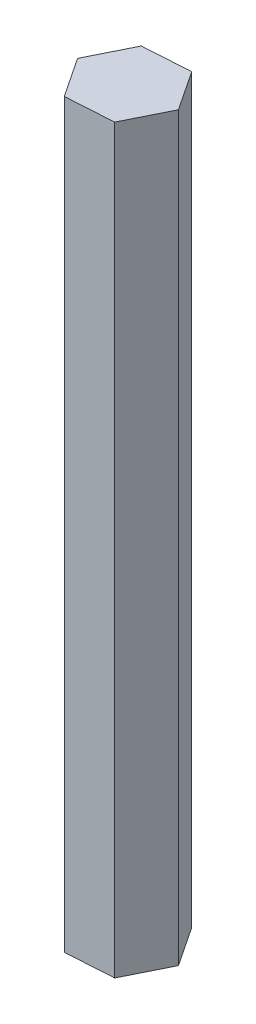
SolidWorks part; units mm, degrees
ref_plane "Front Plane" through (0, 0, 0) normal (0, 0, 1) x (1, 0, 0)
ref_plane "Top Plane" through (0, 0, 0) normal (0, 1, 0) x (1, 0, 0)
ref_plane "Right Plane" through (0, 0, 0) normal (1, 0, 0) x (0, 0, -1)
sketch "Sketch1" plane through (0, 0, 0) normal (0, 1, 0) x (1, 0, 0)
  line L1 (3.2599, 6.5678) -> (-4.0579, 6.1071)
  line L2 (-4.0579, 6.1071) -> (-7.3179, -0.4607)
  line L3 (-7.3179, -0.4607) -> (-3.2599, -6.5678)
  line L4 (-3.2599, -6.5678) -> (4.0579, -6.1071)
  line L5 (4.0579, -6.1071) -> (7.3179, 0.4607)
  line L6 (7.3179, 0.4607) -> (3.2599, 6.5678)
  circle A0 centre (0, 0) radius 6.35 construction
  dimension "D1" = 12.7
extrude "Boss-Extrude1" add sketch "Sketch1" along normal blind 114.3
